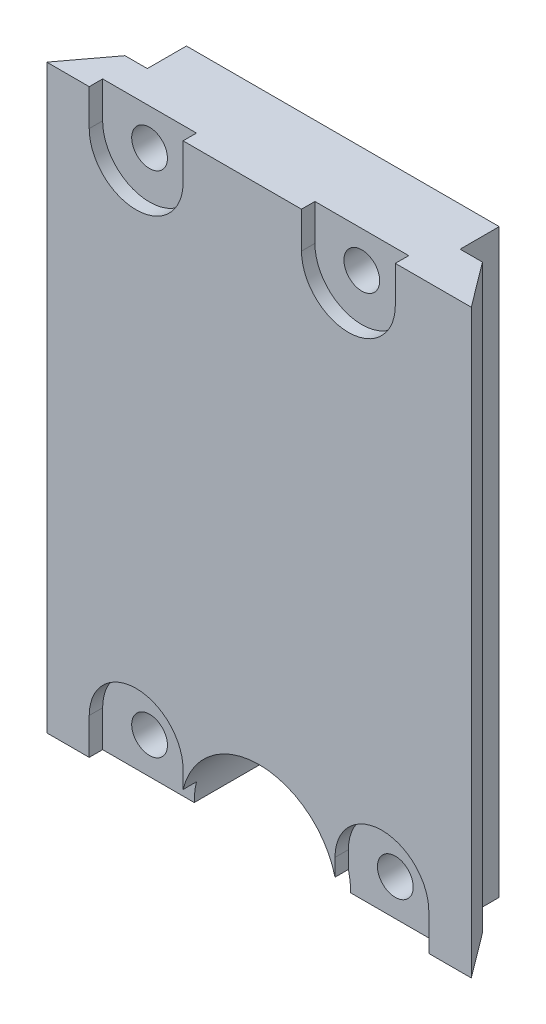
SolidWorks part; units mm, degrees
ref_plane "前视基准面" through (0, 0, 0) normal (0, 0, 1) x (1, 0, 0)
ref_plane "上视基准面" through (0, 0, 0) normal (0, 1, 0) x (1, 0, 0)
ref_plane "右视基准面" through (0, 0, 0) normal (1, 0, 0) x (0, 0, -1)
other "Configuration Table"
sketch "草图2" plane through (0, 0, 0) normal (0, 1, 0) x (1, 0, 0)
  line L0 (0, 0) -> (38, 0)
  line L1 (38, 0) -> (35, 4)
  line L2 (35, 4) -> (3, 4)
  line L3 (3, 4) -> (0, 0)
  line L4 (19, 4) -> (19, 0) construction
  dimension "D1" = 4
  dimension "D2" = 38
  dimension "D3" = 32
extrude "凸台-拉伸1" add sketch "草图2" along normal blind 52
sketch "草图3" plane through (0, 0, -4) normal (0, 0, -1) x (-1, 0, 0)
  line L0 (-35, 52) -> (-3, 52) construction
  line L1 (-33, 52) -> (-5, 52)
  line L2 (-33, 52) -> (-33, 0)
  line L3 (-33, 0) -> (-5, 0)
  line L4 (-5, 52) -> (-5, 0)
  line L5 (-33, 52) -> (-5, 0) construction
  line L6 (-33, 0) -> (-5, 52) construction
  line L7 (-35, 0) -> (-3, 0) construction
  line L8 (-35, 52) -> (-35, 0) construction
  line L9 (-3, 52) -> (-3, 0) construction
  point P4 (-19, 26)
  dimension "D1" = 2
  dimension "D2" = 2
extrude "凸台-拉伸2" add sketch "草图3" along normal blind 3.5
sketch "草图4" plane through (0, 0, 0) normal (0, 0, 1) x (1, 0, 0)
  line L0 (19, 52) -> (19, 0) construction
  line L1 (0, 52) -> (38, 52) construction
  line L2 (0, 0) -> (38, 0) construction
  line L3 (0, 26) -> (38, 26) construction
  line L4 (0, 52) -> (0, 0) construction
  line L5 (38, 52) -> (38, 0) construction
  line L6 (8, 3.25) -> (8, 48.75) construction
  line L7 (8, 48.75) -> (27, 48.75) construction
  circle A0 centre (8, 3.25) radius 1.6
  circle A1 centre (30, 3.25) radius 1.6
  circle A4 centre (8, 48.75) radius 1.6
  circle A5 centre (27, 48.75) radius 1.6
  dimension "D1" = 3.2
  dimension "D4" = 3
  dimension "D2" = 22.75
  dimension "D3" = 11
extrude "切除-拉伸1" cut sketch "草图4" against normal up to next
sketch "草图6" plane through (0, 0, 0) normal (0, 0, 1) x (1, 0, 0)
  circle A0 centre (19, 0.05) radius 7
  circle A1 centre (19, 0.05) radius 3.65 construction
  dimension "D1" = 14
extrude "切除-拉伸2" cut sketch "草图6" against normal through all
sketch "草图7" plane through (0, 0, 0) normal (0, 0, 1) x (1, 0, 0)
  circle A14 centre (8, 48.75) radius 4
  circle A15 centre (27, 48.75) radius 4
  circle A16 centre (8, 3.25) radius 4
  circle A17 centre (30, 3.25) radius 4
  dimension "D1" = 8
extrude "切除-拉伸3" cut sketch "草图7" against normal blind 1.2
sketch "草图8" plane through (0, 0, -1.2) normal (0, 0, 1) x (1, 0, 0)
  line L0 (8, 48.75) -> (8, 52) construction
  line L1 (10.3318, 52) -> (5.6682, 52) construction
  line L2 (3.8, 48.75) -> (3.8, 52)
  line L3 (12.2, 48.75) -> (12.2, 52)
  line L4 (27, 48.75) -> (27, 52) construction
  line L5 (29.3318, 52) -> (24.6682, 52) construction
  line L6 (22.8, 48.75) -> (22.8, 52)
  line L7 (31.2, 48.75) -> (31.2, 52)
  line L8 (8, 3.25) -> (8, 0) construction
  line L9 (10.3318, 0) -> (5.6682, 0) construction
  line L10 (12.2, 3.25) -> (12.2, 0)
  line L11 (3.8, 3.25) -> (3.8, 0)
  line L12 (30, 3.25) -> (30, 0) construction
  line L13 (32.3318, 0) -> (27.6682, 0) construction
  line L14 (34.2, 3.25) -> (34.2, 0)
  line L15 (25.8, 3.25) -> (25.8, 0)
  arc A0 (3.8, 48.75) -> (12.2, 48.75) centre (8, 48.75) ccw
  arc A1 (12.2, 52) -> (3.8, 52) centre (8, 52) ccw
  arc A2 (22.8, 48.75) -> (31.2, 48.75) centre (27, 48.75) ccw
  arc A3 (31.2, 52) -> (22.8, 52) centre (27, 52) ccw
  arc A4 (12.2, 3.25) -> (3.8, 3.25) centre (8, 3.25) ccw
  arc A5 (3.8, 0) -> (12.2, 0) centre (8, 0) ccw
  arc A6 (34.2, 3.25) -> (25.8, 3.25) centre (30, 3.25) ccw
  arc A7 (25.8, 0) -> (34.2, 0) centre (30, 0) ccw
  point P5 (8, 50.375)
  point P10 (27, 50.375)
  point P20 (8, 1.625)
  point P30 (30, 1.625)
  dimension "D1" = 4.2
extrude "切除-拉伸4" cut sketch "草图8" along normal up to next
